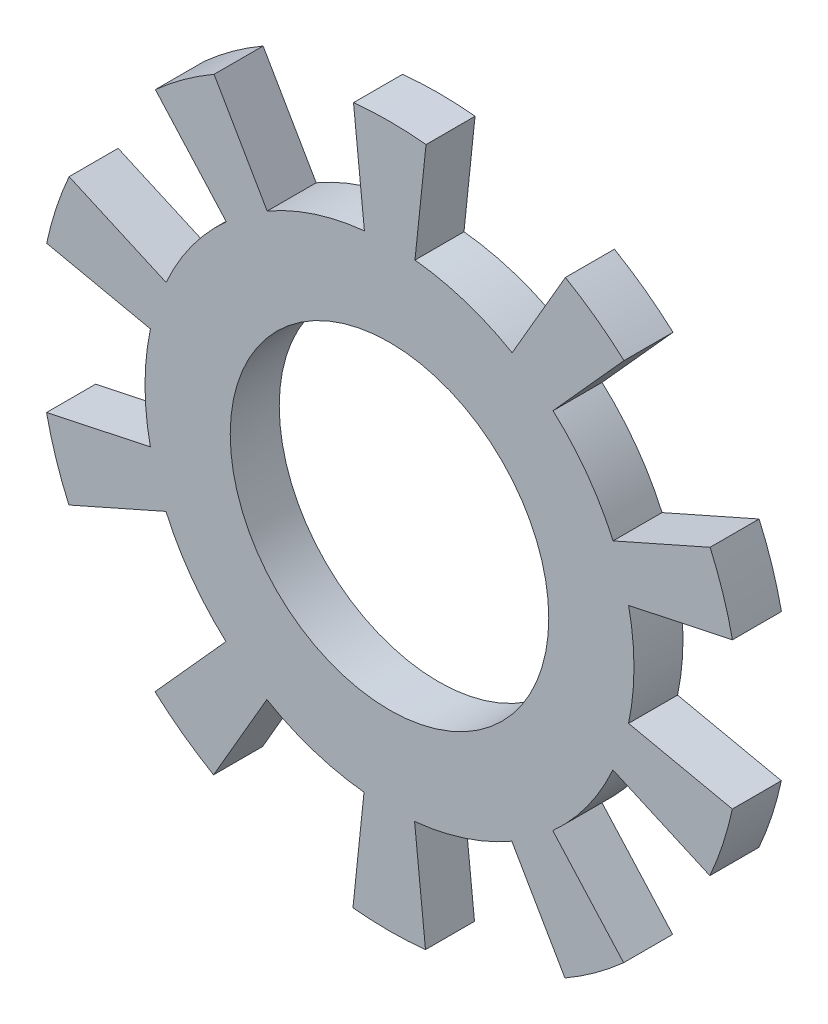
SolidWorks part; units mm, degrees
ref_plane "Front Plane" through (0, 0, 0) normal (0, 0, 1) x (1, 0, 0)
ref_plane "Top Plane" through (0, 0, 0) normal (0, 1, 0) x (1, 0, 0)
ref_plane "Right Plane" through (0, 0, 0) normal (1, 0, 0) x (0, 0, -1)
sketch "Sketch1" plane through (0, 0, 0) normal (0, 0, 1) x (1, 0, 0)
  line L0 (0, 0) -> (-0.9467, -9.0369) construction
  line L1 (0, 0) -> (-4.5583, -7.8602) construction
  line L2 (-0.9467, -9.0369) -> (-0.6601, -6.3011)
  line L3 (-4.5583, -7.8602) -> (-3.1783, -5.4807)
  line L4 (-6.0776, -6.7545) -> (-4.2377, -4.7097)
  line L5 (-8.3078, -3.6798) -> (-5.7928, -2.5658)
  line L6 (-8.8871, -1.8922) -> (-6.1967, -1.3194)
  line L7 (-8.8841, 1.9062) -> (-6.1946, 1.3291)
  line L8 (-8.302, 3.6929) -> (-5.7887, 2.575)
  line L9 (-6.067, 6.7641) -> (-4.2303, 4.7164)
  line L10 (-4.5458, 7.8674) -> (-3.1697, 5.4857)
  line L11 (-0.9324, 9.0383) -> (-0.6502, 6.3022)
  line L12 (0.9467, 9.0369) -> (0.6601, 6.3011)
  line L13 (4.5583, 7.8602) -> (3.1783, 5.4807)
  line L14 (6.0776, 6.7545) -> (4.2377, 4.7097)
  line L15 (8.3078, 3.6798) -> (5.7928, 2.5658)
  line L16 (8.8871, 1.8922) -> (6.1967, 1.3194)
  line L17 (8.8841, -1.9062) -> (6.1946, -1.3291)
  line L18 (8.302, -3.6929) -> (5.7887, -2.575)
  line L19 (6.067, -6.7641) -> (4.2303, -4.7164)
  line L20 (4.5458, -7.8674) -> (3.1697, -5.4857)
  line L21 (0.9324, -9.0383) -> (0.6502, -6.3022)
  circle A0 centre (0, 0) radius 9.0863
  circle A2 centre (0, 0) radius 4.1275
  arc A3 (-4.2377, -4.7097) -> (-5.7928, -2.5658) centre (0, 0) cw
  arc A4 (-6.1967, -1.3194) -> (-6.1946, 1.3291) centre (0, 0) cw
  circle A5 centre (0, 0) radius 6.3356 construction
  arc A6 (-0.6601, -6.3011) -> (-3.1783, -5.4807) centre (0, 0) cw
  arc A7 (-5.7887, 2.575) -> (-4.2303, 4.7164) centre (0, 0) cw
  arc A8 (-3.1697, 5.4857) -> (-0.6502, 6.3022) centre (0, 0) cw
  arc A9 (0.6601, 6.3011) -> (3.1783, 5.4807) centre (0, 0) cw
  arc A10 (4.2377, 4.7097) -> (5.7928, 2.5658) centre (0, 0) cw
  arc A11 (6.1967, 1.3194) -> (6.1946, -1.3291) centre (0, 0) cw
  arc A12 (5.7887, -2.575) -> (4.2303, -4.7164) centre (0, 0) cw
  arc A13 (3.1697, -5.4857) -> (0.6502, -6.3022) centre (0, 0) cw
  point P46 (0, 0)
  point P65 (0, 0)
  dimension "D1" = 8.255
extrude "Boss-Extrude1" add sketch "Sketch1" along normal blind 1.27
